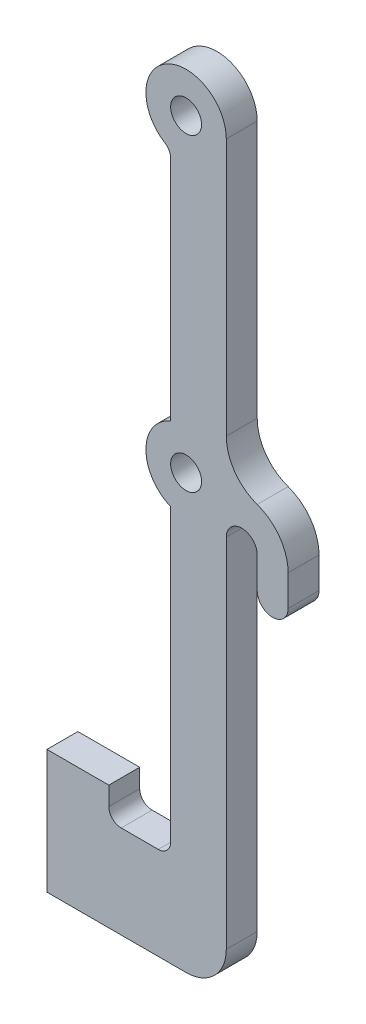
SolidWorks part; units mm, degrees
ref_plane "Front Plane" through (0, 0, 0) normal (0, 0, 1) x (1, 0, 0)
ref_plane "Top Plane" through (0, 0, 0) normal (0, 1, 0) x (1, 0, 0)
ref_plane "Right Plane" through (0, 0, 0) normal (1, 0, 0) x (0, 0, -1)
sketch "Sketch1" plane through (0, 0, 0) normal (0, 0, 1) x (1, 0, 0)
  line L0 (8.255, 0) -> (8.255, -144.145)
  line L1 (-3.175, -7.62) -> (-3.175, -55.88)
  line L2 (-5.715, -133.35) -> (-13.335, -133.35)
  line L3 (-15.875, -130.81) -> (-15.875, -127)
  line L4 (-15.875, -127) -> (-28.575, -127)
  line L5 (-28.575, -127) -> (-28.575, -152.4)
  line L6 (0, 0) -> (0, -144.145) construction
  line L7 (0, -152.4) -> (-28.575, -152.4)
  line L8 (-3.175, -71.12) -> (-3.175, -130.81)
  arc A0 (8.255, 0) -> (-3.175, -7.62) centre (0, 0) ccw
  circle A1 centre (0, 0) radius 3.175
  arc A3 (-13.335, -133.35) -> (-15.875, -130.81) centre (-13.335, -130.81) cw
  arc A4 (-5.715, -133.35) -> (-3.175, -130.81) centre (-5.715, -130.81) ccw
  circle A5 centre (0, -144.145) radius 3.175 construction
  arc A6 (8.255, -144.145) -> (0, -152.4) centre (0, -144.145) cw
  circle A7 centre (0, -63.5) radius 3.175
  arc A8 (-3.175, -55.88) -> (-3.175, -71.12) centre (0, -63.5) ccw
  circle A9 centre (0, -63.5) radius 8.255 construction
  dimension "D1" = 16.51
  dimension "D2" = 2.54
  dimension "D4" = 6.35
  dimension "D7" = 6.35
  dimension "D3" = 12.7
  dimension "D9" = 63.5
  dimension "D5" = 152.4
  dimension "D6" = 6.35
  dimension "D8" = 25.4
  dimension "D12" = 12.7
  dimension "D13" = 6.35
extrude "Boss-Extrude1" add sketch "Sketch1" along normal mid plane 6.35 contours A8 L8 A4 L2 A3 L3 L4 L5 L7 A6 L0
fillet "Fillet1" radius 2.54 1 edges at (-3.175, -7.62, 0)
sketch "Sketch2" plane through (0, 0, 3.175) normal (0, 0, 1) x (1, 0, 0)
  line L1 (14.605, -70.8224) -> (14.605, -77.1724)
  line L2 (8.255, 0) -> (8.255, -144.145) construction
  line L3 (20.955, -77.1724) -> (20.955, -70.8224)
  line L4 (8.255, -52.8619) -> (8.255, -70.8224)
  arc A0 (14.605, -70.8224) -> (8.255, -70.8224) centre (11.43, -70.8224) ccw
  arc A2 (14.605, -77.1724) -> (20.955, -77.1724) centre (17.78, -77.1724) ccw
  arc A3 (20.955, -70.8224) -> (14.605, -61.8422) centre (11.43, -70.8224) ccw
  arc A4 (14.605, -61.8422) -> (8.255, -52.8619) centre (17.78, -52.8619) cw
  dimension "D3" = 3.175
  dimension "D4" = 3.175
  dimension "D1" = 6.35
  dimension "D2" = 6.35
extrude "Boss-Extrude2" add sketch "Sketch2" against normal blind 6.35
